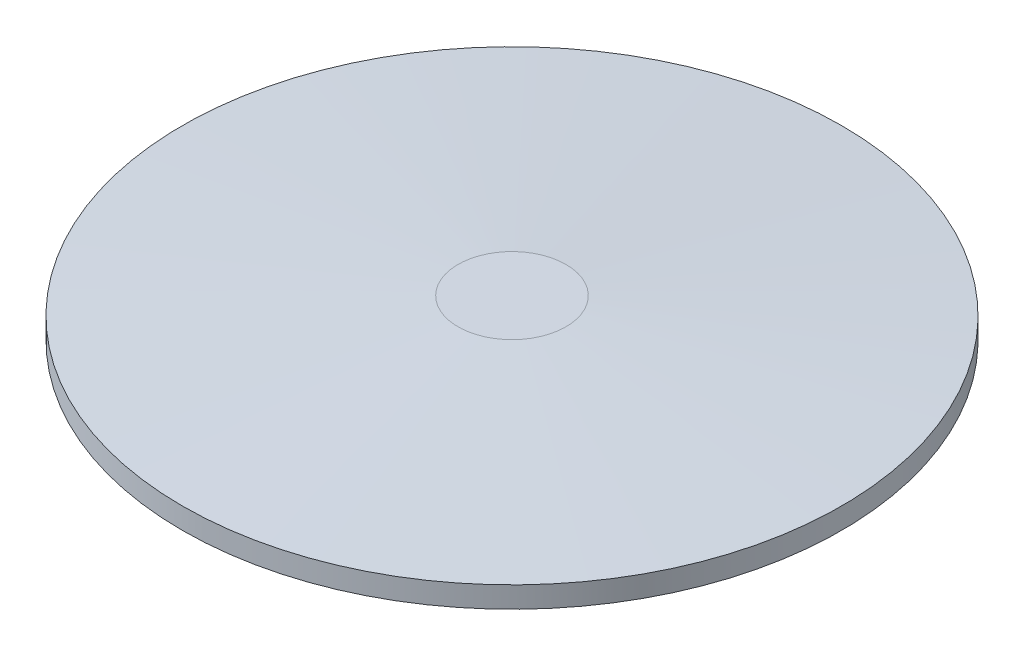
SolidWorks part; units mm, degrees
material "Nylon 6/10"
ref_plane "Front Plane"
ref_plane "Top Plane" through (0, 0, 0) normal (0, 1, 0) x (1, 0, 0)
ref_plane "Right Plane" through (0, 0, 0) normal (1, 0, 0) x (0, 0, -1)
sketch "Sketch1" plane through (0, 0, 0) normal (0, 1, 0) x (1, 0, 0)
  circle A0 centre (0, 0) radius 5.25
  dimension "D1" = 10.5
sketch "Sketch9" plane through (0, 0, 0) normal (0, 0, 1) x (1, 0, 0)
  line L0 (0, 0) -> (0, 1.9349) construction
  line L1 (0, -3.3693) -> (6.1758, -3.3693)
  line L2 (6.1758, -3.3693) -> (6.1758, -2.5835)
  line L3 (6.1758, -2.5835) -> (37.7, -1.2159)
  line L4 (37.7, -1.2159) -> (37.7, 1.2036)
  line L5 (37.7, 1.2036) -> (6.1758, 3.2023)
  line L6 (6.1758, 3.2023) -> (0, 3.2023)
  line L7 (0, -3.3693) -> (0, 3.2023)
  dimension "D1" = 37.7
revolve "Revolve1" add sketch "Sketch9" angle 360 mid plane about L7
